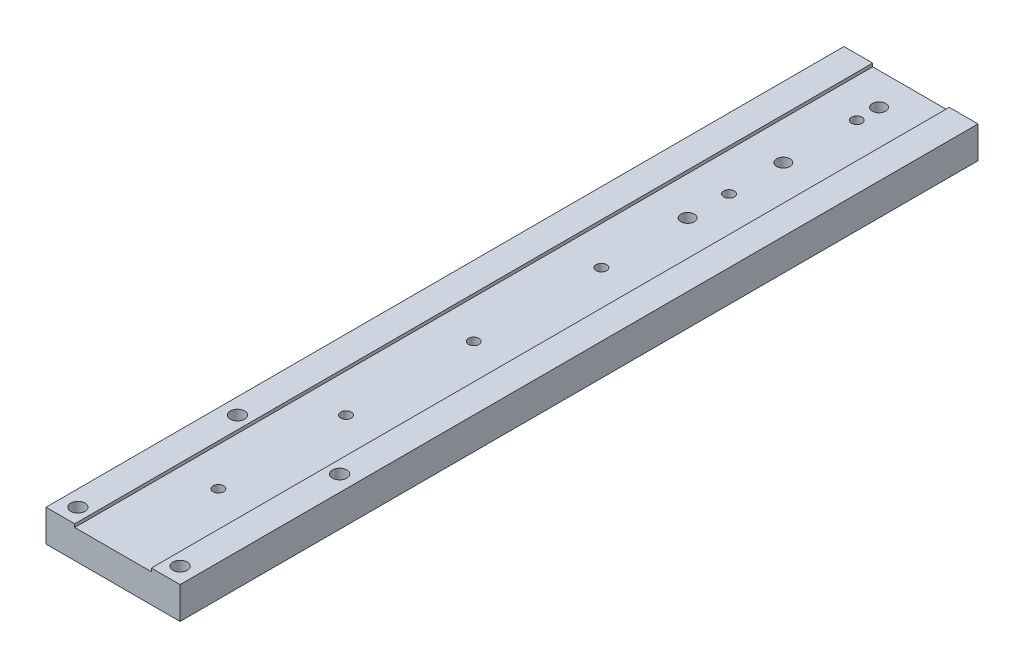
SolidWorks part; units mm, degrees
material "6061"
ref_plane "前视" through (0, 0, 0) normal (0, 0, 1) x (1, 0, 0)
ref_plane "上视" through (0, 0, 0) normal (0, 1, 0) x (1, 0, 0)
ref_plane "右视" through (0, 0, 0) normal (1, 0, 0) x (0, 0, -1)
sketch "草图1" plane through (0, 0, 0) normal (0, 1, 0) x (1, 0, 0)
  line L1 (-21, -125) -> (21, -125)
  line L2 (-21, -125) -> (-21, 125)
  line L3 (-21, 125) -> (21, 125)
  line L4 (21, -125) -> (21, 125)
  line L5 (-21, -125) -> (21, 125) construction
  line L6 (-21, 125) -> (21, -125) construction
  point P0 (0, 0)
  dimension "D1" = 42
  dimension "D2" = 250
extrude "凸台-拉伸1" add sketch "草图1" along normal blind 10
sketch "草图10" plane through (0, 0, -125) normal (0, 0, -1) x (-1, 0, 0)
  line L0 (0, 10) -> (0, 5.8176) construction
  line L1 (-21, 10) -> (21, 10) construction
  line L3 (-12, 9) -> (12, 9)
  line L4 (-12, 9) -> (-12, 10)
  line L5 (-12, 10) -> (12, 10)
  line L6 (12, 9) -> (12, 10)
  line L7 (-12, 9) -> (12, 10) construction
  line L8 (-12, 10) -> (12, 9) construction
  point P5 (0, 9.5)
  dimension "D1" = 24
  dimension "D2" = 1
extrude "切除-拉伸1" cut sketch "草图10" against normal through all
hole_wizard "M4 螺纹孔1" positions "草图3" profile "草图2" tap size "M4" standard "Gb" end condition through all
sketch "草图3" plane through (-1.7254, 9, -76.2896) normal (0, 1, 0) x (1, 0, 0)
  line L0 (1.7254, -192.2896) -> (1.7254, 0) construction
  line L4 (22.7254, 48.7104) -> (13.7254, 48.7104) construction
  point P0 (1.7254, 31.7104)
  dimension "D1" = 17
sketch "草图2" plane through (0, 9, -108) normal (1, 0, 0) x (0, 0, 1)
  line L0 (0, 0) -> (0, 9)
  line L1 (0, 9) -> (1.65, 9)
  line L2 (1.65, 9) -> (1.65, 0)
  line L5 (1.65, 0) -> (0, 0)
  line L11 (0, -6.35) -> (0, 107.95) construction
  dimension "通孔螺纹孔钻头直径" = 3.3
  dimension "通孔螺纹孔钻头深度" = 9
cosmetic thread "孔螺蚊线1" parameters "D2"=4
pattern_linear "阵列(线性)1" count 6 spacing 40 along (0, 0, 1) of "M4 螺纹孔1"
hole_wizard "M5 螺纹孔1" positions "草图5" profile "草图4" tap size "M5" standard "Gb" end condition through all
sketch "草图5" plane through (0, 0, 0) normal (0, -1, 0) x (-1, 0, 0)
  line L1 (-21, 125) -> (21, 125) construction
  line L2 (0, 115) -> (0, 55) construction
  point P0 (0, 55)
  point P2 (0, 115)
  point P13 (0, 85)
  dimension "D1" = 60
  dimension "D2" = 10
sketch "草图4" plane through (0, 0, -55) normal (1, 0, 0) x (0, 0, -1)
  line L0 (0, 0) -> (0, 10)
  line L1 (0, 10) -> (2.1, 10)
  line L2 (2.1, 10) -> (2.1, 0)
  line L5 (2.1, 0) -> (0, 0)
  line L11 (0, -6.35) -> (0, 107.95) construction
  dimension "通孔螺纹孔钻头直径" = 4.2
  dimension "通孔螺纹孔钻头深度" = 10
cosmetic thread "孔螺蚊线2" parameters "D2"=5
cosmetic thread "孔螺蚊线3" parameters "D2"=5
cosmetic thread "孔螺蚊线6" parameters "D2"=5
hole_wizard "打孔尺寸根据内六角圆柱头螺钉的类型1" positions "草图7" profile "草图6" counterbore size "M4" standard "Gb" end condition through all
sketch "草图7" plane through (0, 0, 0) normal (0, -1, 0) x (-1, 0, 0)
  line L0 (0, -125) -> (0, -36.2108) construction
  line L1 (21, -125) -> (-21, -125) construction
  line L4 (-12, -125) -> (-21, -125) construction
  point P0 (16, -120)
  point P2 (16, -70)
  point P12 (-16, -70)
  point P13 (-16, -120)
  point P17 (-16.5, -125)
  dimension "D1" = 32
  dimension "D2" = 50
  dimension "D3" = 5
sketch "草图6" plane through (-16, 0, 120) normal (1, 0, 0) x (0, 0, -1)
  line L0 (0, 0) -> (0, 10)
  line L1 (0, 10) -> (2.25, 10)
  line L3 (2.25, 10) -> (2.25, 4.6)
  line L4 (2.25, 4.6) -> (4, 4.6)
  line L5 (4, 4.6) -> (4, 0)
  line L7 (4, 0) -> (0, 0)
  line L11 (0, -6.35) -> (0, 107.95) construction
  dimension "通孔孔直径" = 4.5
  dimension "通孔孔深度" = 10
  dimension "柱形沉头孔直径" = 8
  dimension "柱形沉头孔深度" = 4.6
hole_wizard "M5 螺纹孔2" positions "草图9" profile "草图8" tap size "M5" standard "Gb"
sketch "草图9" plane through (0, 0, -125) normal (0, 0, -1) x (-1, 0, 0)
  line L0 (0, 10) -> (0, 5) construction
  line L2 (0, 5) -> (-21, 5) construction
  line L3 (-21, 10) -> (-21, 0) construction
  point P0 (-15, 5)
  point P16 (15, 5)
  dimension "D1" = 30
sketch "草图8" plane through (15, 5, -125) normal (1, 0, 0) x (0, 1, 0)
  line L0 (0, 0) -> (0, 13.6618)
  line L1 (0, 13.6618) -> (2.1, 12.4)
  line L2 (2.1, 12.4) -> (2.1, 0)
  line L5 (2.1, 0) -> (0, 0)
  line L10 (0, 13.6618) -> (-2.1, 12.4) construction
  line L11 (0, -6.35) -> (0, 107.95) construction
  dimension "螺纹孔钻头直径" = 4.2
  dimension "螺纹孔钻头深度" = 12.4
  dimension "导头角度" = 118
cosmetic thread "孔螺蚊线4" parameters "D1"=10, "D2"=5
cosmetic thread "孔螺蚊线5" parameters "D1"=10, "D2"=5
